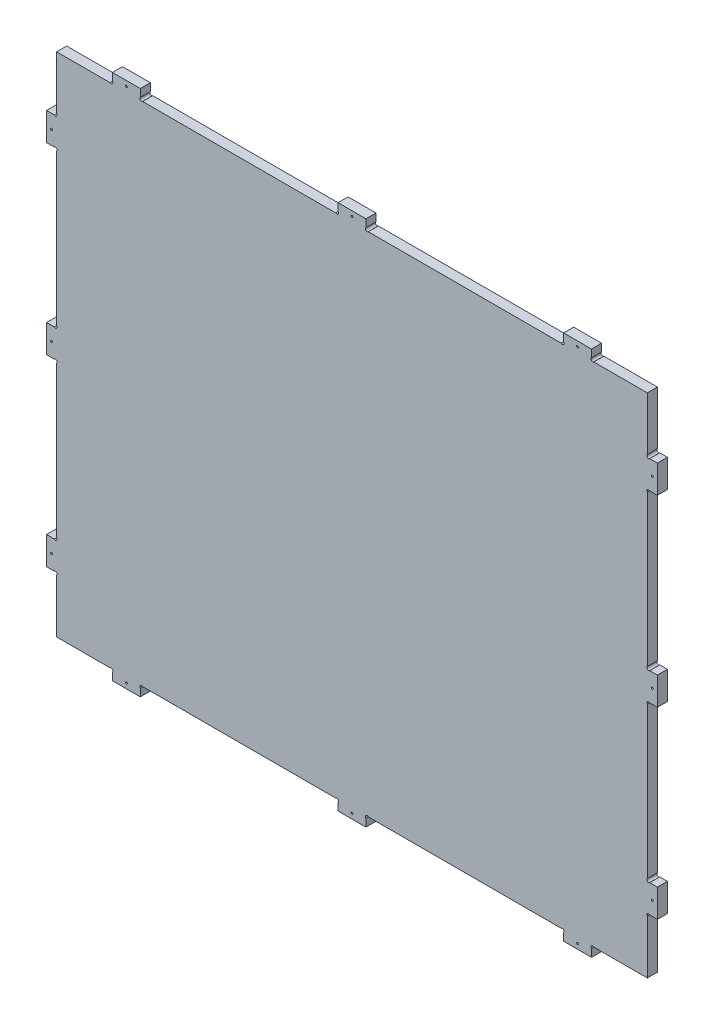
SolidWorks part; units mm, degrees
ref_plane "Front Plane" through (0, 0, 0) normal (0, 0, 1) x (1, 0, 0)
ref_plane "Top Plane" through (0, 0, 0) normal (0, 1, 0) x (1, 0, 0)
ref_plane "Right Plane" through (0, 0, 0) normal (1, 0, 0) x (0, 0, -1)
sketch "Sketch1" plane through (0, 0, 0) normal (0, 0, 1) x (1, 0, 0)
  line L0 (-961.2365, 328.9507) -> (-961.2365, 378.9507)
  line L8 (-943.2365, 807.9015) -> (-943.2365, 707.9015)
  line L9 (-943.2365, 707.9015) -> (-961.2365, 707.9015)
  line L10 (-961.2365, 657.9015) -> (-943.2365, 657.9015)
  line L11 (-943.2365, 657.9015) -> (-943.2365, 378.9507)
  line L12 (-943.2365, 378.9507) -> (-961.2365, 378.9507)
  line L13 (-961.2365, 657.9015) -> (-961.2365, 707.9015)
  line L18 (-414.1183, 825.9015) -> (-414.1183, 353.9507) construction
  line L19 (-961.2365, 353.9507) -> (-414.1183, 353.9507) construction
  line L20 (-943.2365, 807.9015) -> (-843.2365, 807.9015)
  line L21 (-843.2365, 807.9015) -> (-843.2365, 825.9015)
  line L22 (-843.2365, 825.9015) -> (-793.2365, 825.9015)
  line L23 (-793.2365, 825.9015) -> (-793.2365, 807.9015)
  line L24 (-793.2365, 807.9015) -> (-439.1183, 807.9015)
  line L25 (-439.1183, 807.9015) -> (-439.1183, 825.9015)
  line L26 (-843.2365, 603) -> (-843.2365, 0) construction
  line L28 (-439.1183, 825.9015) -> (-389.1183, 825.9015)
  line L29 (-788.166, 707.9015) -> (-779.041, 707.9015) construction
  line L30 (-439.1183, -118) -> (-389.1183, -118)
  line L31 (-439.1183, -100) -> (-439.1183, -118)
  line L32 (-793.2365, -100) -> (-439.1183, -100)
  line L33 (-793.2365, -118) -> (-793.2365, -100)
  line L34 (-843.2365, -118) -> (-793.2365, -118)
  line L35 (-843.2365, -100) -> (-843.2365, -118)
  line L36 (-943.2365, -100) -> (-843.2365, -100)
  line L37 (-961.2365, 50) -> (-961.2365, 0)
  line L38 (-943.2365, 328.9507) -> (-961.2365, 328.9507)
  line L39 (-943.2365, 50) -> (-943.2365, 328.9507)
  line L40 (-961.2365, 50) -> (-943.2365, 50)
  line L41 (-943.2365, 0) -> (-961.2365, 0)
  line L42 (-943.2365, -100) -> (-943.2365, 0)
  line L43 (-841.2365, 0) -> (-832.7445, 0) construction
  line L44 (115, -100) -> (115, 0)
  line L45 (115, 0) -> (133, 0)
  line L46 (133, 50) -> (115, 50)
  line L47 (115, 50) -> (115, 328.9507)
  line L48 (115, 328.9507) -> (133, 328.9507)
  line L49 (133, 50) -> (133, 0)
  line L50 (115, -100) -> (15, -100)
  line L51 (15, -100) -> (15, -118)
  line L52 (15, -118) -> (-35, -118)
  line L53 (-35, -118) -> (-35, -100)
  line L54 (-35, -100) -> (-389.1183, -100)
  line L55 (-389.1183, -100) -> (-389.1183, -118)
  line L56 (-389.1183, 807.9015) -> (-389.1183, 825.9015)
  line L57 (-35, 807.9015) -> (-389.1183, 807.9015)
  line L58 (-35, 825.9015) -> (-35, 807.9015)
  line L59 (15, 825.9015) -> (-35, 825.9015)
  line L60 (15, 807.9015) -> (15, 825.9015)
  line L61 (115, 807.9015) -> (15, 807.9015)
  line L62 (133, 657.9015) -> (133, 707.9015)
  line L63 (115, 378.9507) -> (133, 378.9507)
  line L64 (115, 657.9015) -> (115, 378.9507)
  line L65 (133, 657.9015) -> (115, 657.9015)
  line L66 (115, 707.9015) -> (133, 707.9015)
  line L67 (115, 807.9015) -> (115, 707.9015)
  line L68 (133, 328.9507) -> (133, 378.9507)
  line L69 (15, 603) -> (15, 0) construction
  point P24 (-961.2365, 353.9507)
  point P52 (-414.1183, -118)
  point P65 (133, 353.9507)
  dimension "D6" = 50
  dimension "D7" = 18
  dimension "D10" = 100
  dimension "D2" = 25
  dimension "D3" = 50
  dimension "D4" = 100
  dimension "D5" = 18
  dimension "D9" = 100
  dimension "D11" = 25
  dimension "D12" = 100
  dimension "D8" = 100
  dimension "D13" = 100
extrude "Boss-Extrude1" add sketch "Sketch1" along normal blind 18
sketch "Sketch2" plane through (0, 0, 0) normal (0, 0, -1) x (-1, 0, 0)
  line L0 (15, 30) -> (813.2365, 30)
  line L1 (813.2365, 30) -> (813.2365, 573)
  line L2 (813.2365, 573) -> (15, 573)
  line L3 (15, 573) -> (15, 30)
  line L4 (961.2365, 657.9015) -> (961.2365, 707.9015)
  line L5 (961.2365, 657.9015) -> (961.2365, 707.9015)
  line L6 (961.2365, 707.9015) -> (943.2365, 707.9015)
  line L7 (961.2365, 707.9015) -> (943.2365, 707.9015)
  line L64 (943.2365, 707.9015) -> (943.2365, 807.9015)
  line L65 (943.2365, 707.9015) -> (943.2365, 807.9015)
  line L66 (943.2365, 807.9015) -> (843.2365, 807.9015)
  line L67 (943.2365, 807.9015) -> (843.2365, 807.9015)
  line L68 (843.2365, 807.9015) -> (843.2365, 825.9015)
  line L69 (843.2365, 807.9015) -> (843.2365, 825.9015)
  line L70 (843.2365, 825.9015) -> (793.2365, 825.9015)
  line L71 (843.2365, 825.9015) -> (793.2365, 825.9015)
  line L72 (793.2365, 825.9015) -> (793.2365, 807.9015)
  line L73 (793.2365, 825.9015) -> (793.2365, 807.9015)
  line L74 (793.2365, 807.9015) -> (439.1183, 807.9015)
  line L75 (793.2365, 807.9015) -> (439.1183, 807.9015)
  line L76 (439.1183, 807.9015) -> (439.1183, 825.9015)
  line L77 (439.1183, 807.9015) -> (439.1183, 825.9015)
  line L78 (439.1183, 825.9015) -> (389.1183, 825.9015)
  line L79 (439.1183, 825.9015) -> (389.1183, 825.9015)
  line L80 (389.1183, 825.9015) -> (389.1183, 807.9015)
  line L81 (389.1183, 825.9015) -> (389.1183, 807.9015)
  line L82 (389.1183, 807.9015) -> (35, 807.9015)
  line L83 (389.1183, 807.9015) -> (35, 807.9015)
  line L84 (35, 807.9015) -> (35, 825.9015)
  line L85 (35, 807.9015) -> (35, 825.9015)
  line L86 (35, 825.9015) -> (-15, 825.9015)
  line L87 (35, 825.9015) -> (-15, 825.9015)
  line L88 (-15, 825.9015) -> (-15, 807.9015)
  line L89 (-15, 825.9015) -> (-15, 807.9015)
  line L90 (-15, 807.9015) -> (-115, 807.9015)
  line L91 (-15, 807.9015) -> (-115, 807.9015)
  line L92 (-115, 807.9015) -> (-115, 707.9015)
  line L93 (-115, 807.9015) -> (-115, 707.9015)
  line L94 (-115, 707.9015) -> (-133, 707.9015)
  line L95 (-115, 707.9015) -> (-133, 707.9015)
  line L96 (-133, 707.9015) -> (-133, 657.9015)
  line L97 (-133, 707.9015) -> (-133, 657.9015)
  line L98 (-133, 657.9015) -> (-115, 657.9015)
  line L99 (-133, 657.9015) -> (-115, 657.9015)
  line L100 (-115, 657.9015) -> (-115, 378.9507)
  line L101 (-115, 657.9015) -> (-115, 378.9507)
  line L102 (-115, 378.9507) -> (-133, 378.9507)
  line L103 (-115, 378.9507) -> (-133, 378.9507)
  line L104 (-133, 378.9507) -> (-133, 328.9507)
  line L105 (-133, 378.9507) -> (-133, 328.9507)
  line L106 (-133, 328.9507) -> (-115, 328.9507)
  line L107 (-133, 328.9507) -> (-115, 328.9507)
  line L108 (-115, 328.9507) -> (-115, 50)
  line L109 (-115, 328.9507) -> (-115, 50)
  line L110 (-115, 50) -> (-133, 50)
  line L111 (-115, 50) -> (-133, 50)
  line L112 (-133, 50) -> (-133, 0)
  line L113 (-133, 50) -> (-133, 0)
  line L114 (-133, 0) -> (-115, 0)
  line L115 (-133, 0) -> (-115, 0)
  line L116 (-115, 0) -> (-115, -100)
  line L117 (-115, 0) -> (-115, -100)
  line L118 (-115, -100) -> (-15, -100)
  line L119 (-115, -100) -> (-15, -100)
  line L120 (-15, -100) -> (-15, -118)
  line L121 (-15, -100) -> (-15, -118)
  line L122 (-15, -118) -> (35, -118)
  line L123 (-15, -118) -> (35, -118)
  line L124 (35, -118) -> (35, -100)
  line L125 (35, -118) -> (35, -100)
  line L126 (35, -100) -> (389.1183, -100)
  line L127 (35, -100) -> (389.1183, -100)
  line L128 (389.1183, -100) -> (389.1183, -118)
  line L129 (389.1183, -100) -> (389.1183, -118)
  line L130 (389.1183, -118) -> (439.1183, -118)
  line L131 (389.1183, -118) -> (439.1183, -118)
  line L132 (439.1183, -118) -> (439.1183, -100)
  line L133 (439.1183, -118) -> (439.1183, -100)
  line L134 (439.1183, -100) -> (793.2365, -100)
  line L135 (439.1183, -100) -> (793.2365, -100)
  line L136 (793.2365, -100) -> (793.2365, -118)
  line L137 (793.2365, -100) -> (793.2365, -118)
  line L138 (793.2365, -118) -> (843.2365, -118)
  line L139 (793.2365, -118) -> (843.2365, -118)
  line L140 (843.2365, -118) -> (843.2365, -100)
  line L141 (843.2365, -118) -> (843.2365, -100)
  line L142 (843.2365, -100) -> (943.2365, -100)
  line L143 (843.2365, -100) -> (943.2365, -100)
  line L144 (943.2365, -100) -> (943.2365, 0)
  line L145 (943.2365, -100) -> (943.2365, 0)
  line L146 (943.2365, 0) -> (961.2365, 0)
  line L147 (943.2365, 0) -> (961.2365, 0)
  line L148 (961.2365, 0) -> (961.2365, 50)
  line L149 (961.2365, 0) -> (961.2365, 50)
  line L150 (961.2365, 50) -> (943.2365, 50)
  line L151 (961.2365, 50) -> (943.2365, 50)
  line L152 (943.2365, 50) -> (943.2365, 328.9507)
  line L153 (943.2365, 50) -> (943.2365, 328.9507)
  line L154 (943.2365, 328.9507) -> (961.2365, 328.9507)
  line L155 (943.2365, 328.9507) -> (961.2365, 328.9507)
  line L156 (961.2365, 328.9507) -> (961.2365, 378.9507)
  line L157 (961.2365, 328.9507) -> (961.2365, 378.9507)
  line L158 (961.2365, 378.9507) -> (943.2365, 378.9507)
  line L159 (961.2365, 378.9507) -> (943.2365, 378.9507)
  line L160 (943.2365, 378.9507) -> (943.2365, 657.9015)
  line L161 (943.2365, 378.9507) -> (943.2365, 657.9015)
  line L162 (943.2365, 657.9015) -> (961.2365, 657.9015)
  line L163 (943.2365, 657.9015) -> (961.2365, 657.9015)
  dimension "D1" = 0
extrude "Cut-Extrude1" [suppressed] cut sketch "Sketch2" against normal through all flip side to cut
sketch "Sketch3" [suppressed] plane through (0, 0, 0) normal (0, 0, -1) x (-1, 0, 0)
  line L0 (15, 603) -> (15, 0) construction
  line L1 (813.2365, 573) -> (15, 573)
  line L2 (813.2365, 573) -> (813.2365, 562.1515)
  line L3 (813.2365, 562.1515) -> (15, 562.1515)
  line L4 (15, 573) -> (15, 562.1515)
  line L5 (215.9071, 592.1515) -> (206.7821, 592.1515) construction
  dimension "D1" = 30
extrude "Boss-Extrude2" [suppressed] add sketch "Sketch3" against normal up to surface (18 mm away)
sketch "Sketch4" plane through (0, 0, 18) normal (0, 0, 1) x (1, 0, 0)
  line L0 (-843.2365, 807.9015) -> (-878.7542, 843.4191) construction
  line L1 (-793.2365, 807.9015) -> (-757.7189, 843.4191) construction
  line L2 (-414.1183, 825.9015) -> (-414.1183, 662.0131) construction
  line L3 (-389.1183, 825.9015) -> (-439.1183, 825.9015) construction
  line L4 (-35, 807.9015) -> (-70.5176, 843.4191) construction
  line L5 (15, 807.9015) -> (50.5176, 843.4191) construction
  line L6 (-439.1183, 807.9015) -> (-474.6359, 843.4191) construction
  line L7 (-389.1183, 807.9015) -> (-353.6006, 843.4191) construction
  line L8 (-961.2365, 353.9507) -> (-747.8626, 353.9507) construction
  line L9 (-961.2365, 378.9507) -> (-961.2365, 328.9507) construction
  line L10 (-389.1183, -100) -> (-353.6006, -135.5176) construction
  line L11 (-439.1183, -100) -> (-474.6359, -135.5176) construction
  line L12 (15, -100) -> (50.5176, -135.5176) construction
  line L13 (-35, -100) -> (-70.5176, -135.5176) construction
  line L14 (-414.1183, -118) -> (-414.1183, 45.8883) construction
  line L15 (-793.2365, -100) -> (-757.7189, -135.5176) construction
  line L16 (-843.2365, -100) -> (-878.7542, -135.5176) construction
  line L17 (115, 378.9507) -> (150.5176, 414.4684) construction
  line L18 (115, 328.9507) -> (150.5176, 293.4331) construction
  line L19 (115, 707.9015) -> (150.5176, 743.4191) construction
  line L20 (115, 657.9015) -> (150.5176, 622.3838) construction
  line L21 (133, 353.9507) -> (-30.8883, 353.9507) construction
  line L22 (115, 50) -> (150.5176, 85.5176) construction
  line L23 (115, 0) -> (150.5176, -35.5176) construction
  line L24 (-943.2365, 0) -> (-978.7542, -35.5176) construction
  line L25 (-943.2365, 50) -> (-978.7542, 85.5176) construction
  line L26 (-961.2365, 353.9507) -> (-797.3482, 353.9507) construction
  line L27 (-943.2365, 657.9015) -> (-978.7542, 622.3838) construction
  line L28 (-943.2365, 707.9015) -> (-978.7542, 743.4191) construction
  line L29 (-943.2365, 328.9507) -> (-978.7542, 293.4331) construction
  line L30 (-943.2365, 378.9507) -> (-978.7542, 414.4684) construction
  circle A0 centre (-845.3578, 810.0228) radius 3
  circle A1 centre (-791.1152, 810.0228) radius 3
  circle A2 centre (-37.1213, 810.0228) radius 3
  circle A3 centre (17.1213, 810.0228) radius 3
  circle A4 centre (-441.2396, 810.0228) radius 3
  circle A5 centre (-386.9969, 810.0228) radius 3
  circle A6 centre (-386.9969, -102.1213) radius 3
  circle A7 centre (-441.2396, -102.1213) radius 3
  circle A8 centre (17.1213, -102.1213) radius 3
  circle A9 centre (-37.1213, -102.1213) radius 3
  circle A10 centre (-791.1152, -102.1213) radius 3
  circle A11 centre (-845.3578, -102.1213) radius 3
  circle A12 centre (117.1213, 381.0721) radius 3
  circle A13 centre (117.1213, 326.8294) radius 3
  circle A14 centre (117.1213, 710.0228) radius 3
  circle A15 centre (117.1213, 655.7802) radius 3
  circle A16 centre (117.1213, 52.1213) radius 3
  circle A17 centre (117.1213, -2.1213) radius 3
  circle A18 centre (-945.3578, -2.1213) radius 3
  circle A19 centre (-945.3578, 52.1213) radius 3
  circle A20 centre (-945.3578, 655.7802) radius 3
  circle A21 centre (-945.3578, 710.0228) radius 3
  circle A22 centre (-945.3578, 326.8294) radius 3
  circle A23 centre (-945.3578, 381.0721) radius 3
  dimension "D1" = 6
  dimension "D2" = 6
  dimension "D3" = 6
  dimension "D4" = 6
extrude "Cut-Extrude2" cut sketch "Sketch4" against normal blind 30
hole_wizard "M3 Clearance Hole1" positions "Sketch5" profile "Sketch6" hole size "M3" standard "ISO" end condition through all
sketch "Sketch5" plane through (0, 0, 0) normal (0, 0, -1) x (-1, 0, 0)
  point P0 (-124, 682.9015)
  point P2 (-124, 353.9507)
  point P4 (-124, 25)
  point P6 (10, -109)
  point P8 (414.1183, -109)
  point P10 (818.2365, -109)
  point P12 (952.2365, 25)
  point P14 (952.2365, 353.9507)
  point P16 (952.2365, 682.9015)
  point P18 (818.2365, 816.9015)
  point P20 (414.1183, 816.9015)
  point P22 (10, 816.9015)
sketch "Sketch6" plane through (124, 682.9015, 0) normal (1, 0, 0) x (0, 1, 0)
  line L0 (0, 0) -> (0, 18)
  line L1 (0, 18) -> (1.7, 18)
  line L2 (1.7, 18) -> (1.7, 0)
  line L5 (1.7, 0) -> (0, 0)
  line L11 (0, -6.35) -> (0, 107.95) construction
  dimension "Thru Hole Dia." = 3.4
  dimension "Thru Hole Depth" = 18
equation "\"fingerlenght\"=50"
equation "\"D6@Sketch1\"=\"fingerlenght\""
equation "\"fingerendclearance\"=100"
equation "\"osbthickness\"=18"
equation "\"D7@Sketch1\"=\"osbthickness\""
equation "\"D2@Sketch1\"=\"fingerlenght\"/2"
equation "\"D3@Sketch1\"=\"fingerlenght\""
equation "\"D4@Sketch1\"=\"fingerendclearance\""
equation "\"D5@Sketch1\"=\"osbthickness\""
equation "\"D9@Sketch1\"=\"fingerendclearance\""
equation "\"D11@Sketch1\"=\"fingerlenght\"/2"
equation "\"wallclearance\"=100"
equation "\"D12@Sketch1\"=\"wallclearance\""
equation "\"D10@Sketch1\"=\"wallclearance\""
equation "\"D13@Sketch1\"=\"wallclearance\""
